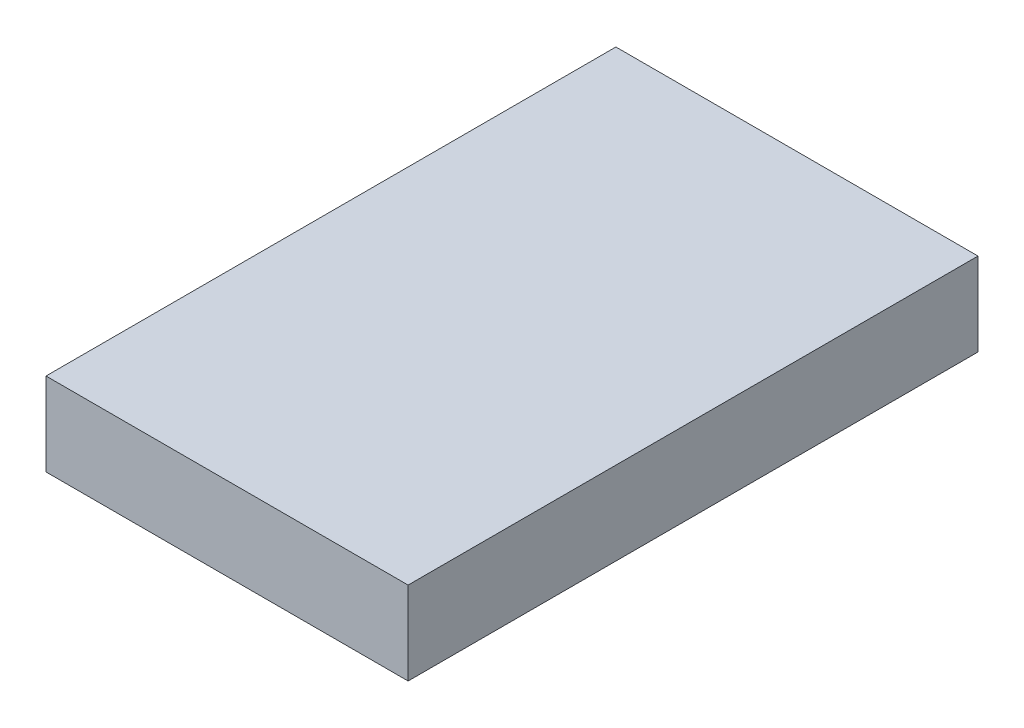
SolidWorks part; units mm, degrees
material "A-Glass Fiber"
ref_plane "Front Plane" through (0, 0, 0) normal (0, 0, 1) x (1, 0, 0)
ref_plane "Top Plane" through (0, 0, 0) normal (0, 1, 0) x (1, 0, 0)
ref_plane "Right Plane" through (0, 0, 0) normal (1, 0, 0) x (0, 0, -1)
sketch "Sketch1" plane through (0, 0, 0) normal (0, 1, 0) x (1, 0, 0)
  line L1 (-193.675, 304.8) -> (193.675, 304.8)
  line L2 (-193.675, 304.8) -> (-193.675, -304.8)
  line L3 (-193.675, -304.8) -> (193.675, -304.8)
  line L4 (193.675, 304.8) -> (193.675, -304.8)
  line L5 (-193.675, 304.8) -> (193.675, -304.8) construction
  line L6 (-193.675, -304.8) -> (193.675, 304.8) construction
  point P0 (0, 0)
  dimension "D1" = 387.35
  dimension "D2" = 609.6
extrude "Boss-Extrude1" add sketch "Sketch1" along normal blind 88.9
